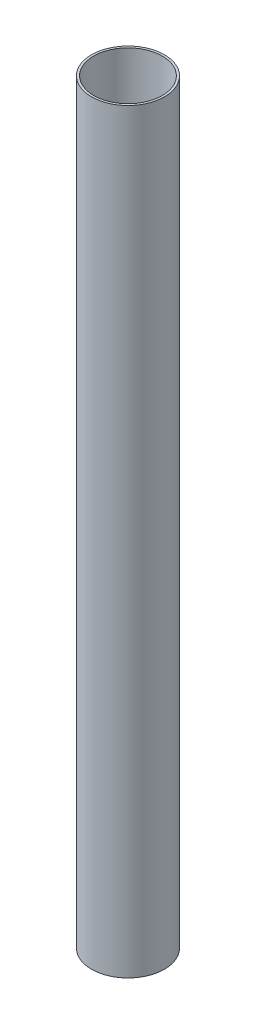
SolidWorks part; units mm, degrees
ref_plane "Front Plane" through (0, 0, 0) normal (0, 0, 1) x (1, 0, 0)
ref_plane "Top Plane" through (0, 0, 0) normal (0, 1, 0) x (1, 0, 0)
ref_plane "Right Plane" through (0, 0, 0) normal (1, 0, 0) x (0, 0, -1)
sketch "Sketch1" plane through (0, 0, 0) normal (0, 0, 1) x (1, 0, 0)
  line L1 (49.53, 1092.2) -> (52.705, 1092.2)
  line L2 (49.53, 1092.2) -> (49.53, 0)
  line L3 (49.53, 0) -> (52.705, 0)
  line L4 (52.705, 1092.2) -> (52.705, 0)
  point P4 (53.5416, 0)
  point P7 (0, 0)
  dimension "D1" = 0
  dimension "D2" = 49.53
  dimension "D3" = 3.175
  dimension "D4" = 1092.2
ref_axis "Central Axis" through (0, 1146.81, 0) along (0, -1, 0)
revolve "Revolve1" add sketch "Sketch1" angle 360 about axis through (0, 1146.81, 0) along (0, -1, 0)
ref_plane "fin plane 1" through (0, 0, 0) normal (-0.866, 0, 0.5) x (0, -1, 0)
ref_plane "fin plane 2" through (0, 0, 0) normal (0.866, 0, 0.5) x (0, -1, 0)
